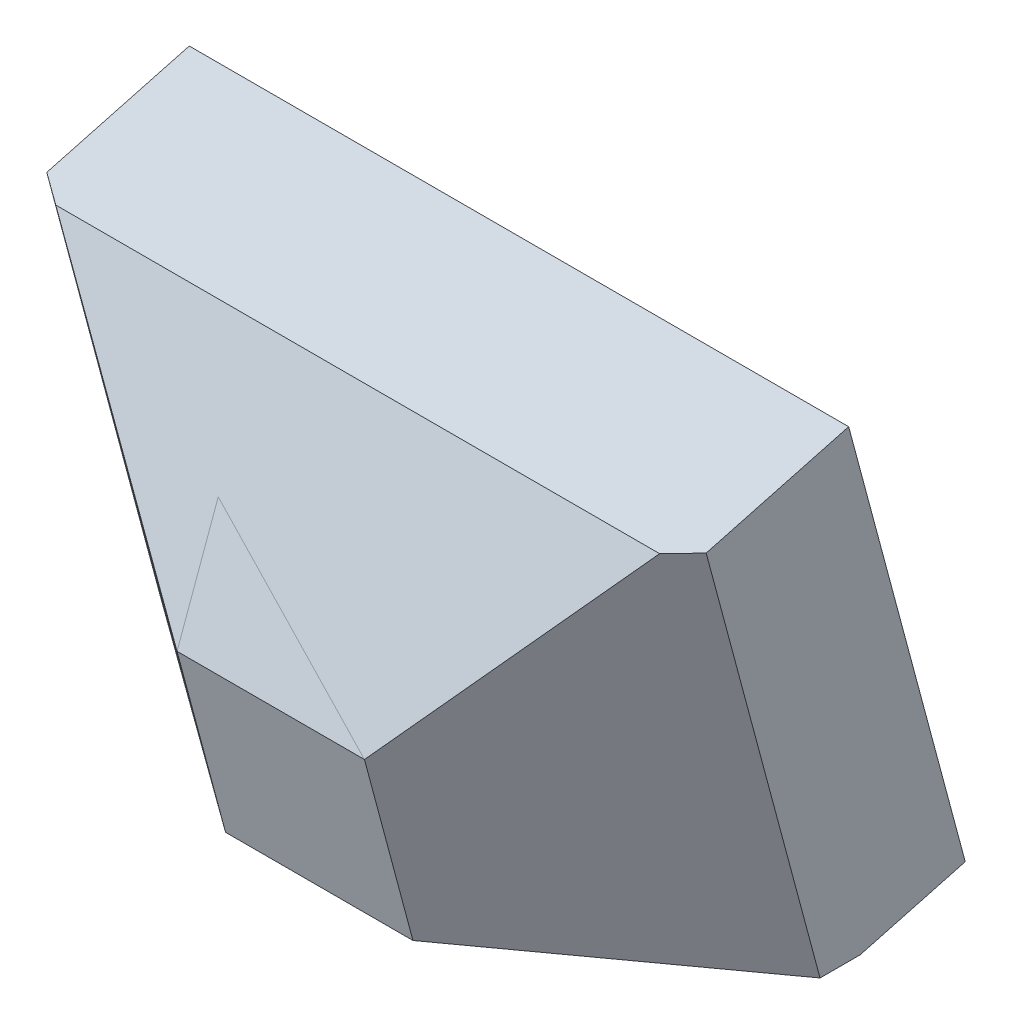
SolidWorks part; units mm, degrees
ref_plane "Front Plane" through (0, 0, 0) normal (0, 0, 1) x (1, 0, 0)
ref_plane "Top Plane" through (0, 0, 0) normal (0, 1, 0) x (1, 0, 0)
ref_plane "Right Plane" through (0, 0, 0) normal (1, 0, 0) x (0, 0, -1)
sketch "Sketch3" plane through (0, 0, 0) normal (1, 0, 0) x (0, 0, -1)
  line L0 (0, 0) -> (-34.9406, 130.4)
  line L1 (0, 0) -> (152.2025, 0)
  line L2 (-34.9406, 130.4) -> (27.6889, 302.4729)
  line L3 (27.6889, 302.4729) -> (152.2025, 302.4729)
  line L4 (-34.9406, 130.4) -> (-73.7634, 275.2889) construction
  line L5 (-73.7634, 275.2889) -> (27.6889, 302.4729) construction
  line L6 (152.2025, 302.4729) -> (152.2025, 0)
  point P3 (0, 0)
  point P9 (152.2025, 302.4729)
  dimension "D1" = 135
  dimension "D2" = 145
  dimension "D3" = 105
  dimension "D4" = 150
extrude "Boss-Extrude3" add sketch "Sketch3" along normal blind 135
ref_plane "Plane1" through (0, 130.4, 34.9406) normal (0, 0.9659, 0.2588) x (-1, 0, 0)
sketch "Sketch4" plane through (0, 130.4, 34.9406) normal (0, 0.9659, 0.2588) x (-1, 0, 0)
  line L0 (-305, -119.0353) -> (-135, 0)
  line L1 (-135, 0) -> (0, 0)
  line L2 (0, 0) -> (170, -119.0353)
  line L3 (0, 0) -> (170, 0) construction
  line L4 (-135, 0) -> (-305, 0) construction
  line L5 (-305, -119.0353) -> (-305, -225.3021)
  line L6 (-305, -225.3021) -> (170, -225.3021)
  line L7 (170, -225.3021) -> (170, -119.0353)
  line L8 (-135, -225.3021) -> (0, -225.3021) construction
  dimension "D1" = 145
  dimension "D2" = 145
  dimension "D3" = 170
extrude "Boss-Extrude4" add sketch "Sketch4" against normal up to vertex (174.3929 mm away) and the other way up to vertex (150 mm away) separate body contours L1 L2 L7 L6 L5 L0
sketch "Sketch5" plane through (0, 0, 0) normal (0, 1, 0) x (1, 0, 0)
  line L1 (-187.7615, 249.1056) -> (349.3117, 249.1056)
  line L2 (-187.7615, 249.1056) -> (-187.7615, -73.6694)
  line L3 (-187.7615, -73.6694) -> (349.3117, -73.6694)
  line L4 (349.3117, 249.1056) -> (349.3117, -73.6694)
  line L5 (-187.7615, 249.1056) -> (349.3117, -73.6694) construction
  line L6 (-187.7615, -73.6694) -> (349.3117, 249.1056) construction
  point P4 (80.7751, 87.7181)
  point P6 (349.3117, 227.8207)
  point P7 (-170, 227.8207)
  point P8 (-190.0372, 233.934)
  point P9 (-187.7615, 249.1056)
extrude "Cut-Extrude1" cut sketch "Sketch5" against normal through all
sketch "Sketch6" plane through (0, 0, 0) normal (1, 0, 0) x (0, 0, -1)
  line L0 (-34.9406, 130.4) -> (35.5604, 324.0997)
  line L3 (-80.9933, 302.2709) -> (-34.9406, 130.4)
  line L4 (0, 0) -> (-73.7634, 275.2889) construction
  line L5 (-80.9933, 302.2709) -> (35.5604, 324.0997)
  dimension "D1" = 35
extrude "Cut-Extrude2" cut sketch "Sketch6" against normal through all and the other way through all
